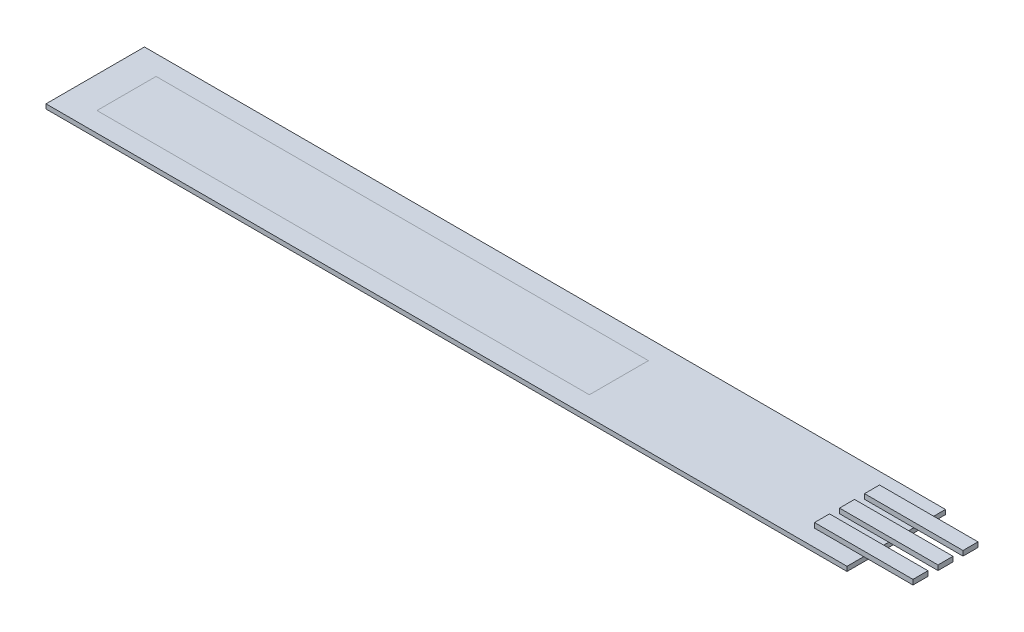
SolidWorks part; units mm, degrees
ref_plane "Front Plane" through (0, 0, 0) normal (0, 0, 1) x (1, 0, 0)
ref_plane "Top Plane" through (0, 0, 0) normal (0, 1, 0) x (1, 0, 0)
ref_plane "Right Plane" through (0, 0, 0) normal (1, 0, 0) x (0, 0, -1)
sketch "Sketch1" plane through (0, 0, 0) normal (0, 1, 0) x (1, 0, 0)
  line L1 (0, 5) -> (56.35, 5)
  line L2 (0, 5) -> (0, -5)
  line L3 (0, -5) -> (56.35, -5)
  line L4 (56.35, 5) -> (56.35, -5) construction
  line L5 (56.35, 5) -> (81.35, 5)
  line L6 (56.35, 5) -> (56.35, -5) construction
  line L7 (56.35, -5) -> (81.35, -5)
  line L8 (81.35, 5) -> (81.35, -5)
  line L9 (3.18, 3) -> (53.18, 3)
  line L10 (3.18, 3) -> (3.18, -3)
  line L11 (3.18, -3) -> (53.18, -3)
  line L12 (53.18, 3) -> (53.18, -3)
  point P4 (0, 0)
  point P13 (3.18, 0)
  dimension "D1" = 10
  dimension "D2" = 56.35
  dimension "D3" = 25
  dimension "D4" = 3.17
  dimension "D5" = 6
  dimension "D6" = 50
extrude "Boss-Extrude1" add sketch "Sketch1" along normal blind 0.46
sketch "Sketch2" plane through (0, 0.46, 0) normal (0, 1, 0) x (1, 0, 0)
  line L0 (53.18, 3) -> (3.18, 3) construction
  line L1 (53.18, -3) -> (53.18, 3) construction
  line L2 (3.18, -3) -> (53.18, -3) construction
  line L3 (3.18, 3) -> (3.18, -3) construction
  line L4 (53.18, 3) -> (3.18, 3)
  line L5 (53.18, -3) -> (53.18, 3)
  line L6 (3.18, -3) -> (53.18, -3)
  line L7 (3.18, 3) -> (3.18, -3)
extrude "Boss-Extrude2" add sketch "Sketch2" against normal up to surface (0.46 mm away) separate body up to face at (40.675, 0, 0)
sketch "Sketch3" plane through (0, 0.46, 0) normal (0, 1, 0) x (1, 0, 0)
  line L0 (86.35, 2.54) -> (76.35, 2.54) construction
  line L1 (76.35, 3.3011) -> (86.35, 3.3011)
  line L2 (76.35, 3.3011) -> (76.35, 1.7789)
  line L3 (76.35, 1.7789) -> (86.35, 1.7789)
  line L4 (86.35, 3.3011) -> (86.35, 1.7789)
  line L5 (76.35, 0.7611) -> (86.35, 0.7611)
  line L6 (76.35, 0.7611) -> (76.35, -0.7611)
  line L7 (76.35, -0.7611) -> (86.35, -0.7611)
  line L8 (86.35, 0.7611) -> (86.35, -0.7611)
  line L9 (76.35, -1.7789) -> (86.35, -1.7789)
  line L10 (76.35, -1.7789) -> (76.35, -3.3011)
  line L11 (76.35, -3.3011) -> (86.35, -3.3011)
  line L12 (86.35, -1.7789) -> (86.35, -3.3011)
  line L13 (86.35, 0) -> (76.35, 0) construction
  line L14 (86.35, -2.54) -> (76.35, -2.54) construction
  line L15 (53.18, -3) -> (53.18, 3) construction
  line L16 (81.35, -5) -> (81.35, 5) construction
  point P21 (53.18, 0)
  dimension "D1" = 1.5222
  dimension "D2" = 1.5222
  dimension "D3" = 1.5222
  dimension "D4" = 10
  dimension "D5" = 2.54
  dimension "D6" = 2.54
  dimension "D7" = 5
extrude "Boss-Extrude3" add sketch "Sketch3" along normal blind 0.5
equation "\"D2@Sketch3\"=\"D1@Sketch3\""
equation "\"D3@Sketch3\"=\"D1@Sketch3\""
